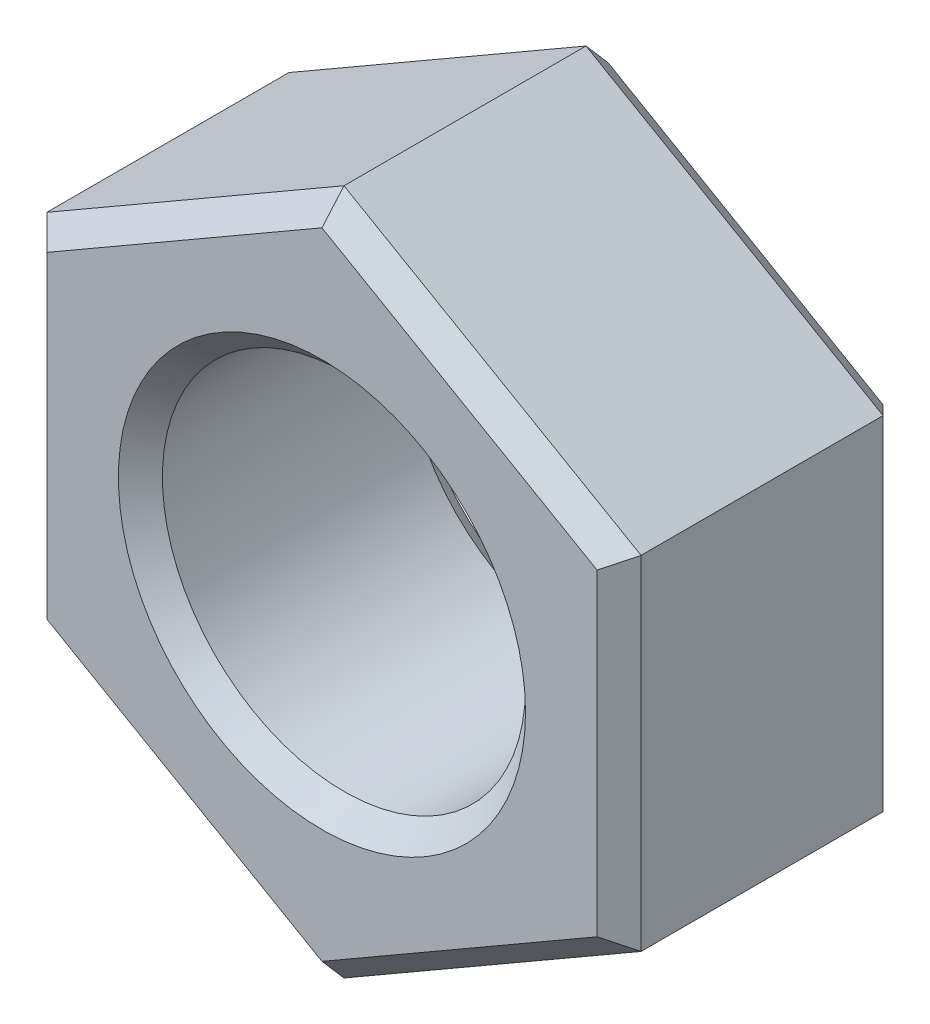
SolidWorks part; units mm, degrees
ref_plane "Front" through (0, 0, 0) normal (0, 0, 1) x (1, 0, 0)
ref_plane "Top" through (0, 0, 0) normal (0, 1, 0) x (1, 0, 0)
ref_plane "Right" through (0, 0, 0) normal (1, 0, 0) x (0, 0, -1)
sketch "Sketch1" plane through (0, 0, 0) normal (0, 0, 1) x (1, 0, 0)
  line L1 (2.7, -1.5588) -> (2.7, 1.5588)
  line L2 (2.7, 1.5588) -> (0, 3.1177)
  line L3 (0, 3.1177) -> (-2.7, 1.5588)
  line L4 (-2.7, 1.5588) -> (-2.7, -1.5588)
  line L5 (-2.7, -1.5588) -> (0, -3.1177)
  line L6 (0, -3.1177) -> (2.7, -1.5588)
  circle A0 centre (0, 0) radius 2.7 construction
  circle A1 centre (0, 0) radius 1.65
  dimension "D1" = 3.3
  dimension "D2" = 5.4
extrude "Boss-Extrude1" add sketch "Sketch1" along normal mid plane 2.6
chamfer "Deburs" distance 0.2 angle 45 14 edges at (1.65, 0, -1.3) (2.7, 0, -1.3) (1.35, 2.3383, -1.3) (-1.35, 2.3383, -1.3) (-2.7, 0, -1.3) (-1.35, -2.3383, -1.3) (1.35, -2.3383, -1.3) (1.65, 0, 1.3) (-1.35, -2.3383, 1.3) (-2.7, 0, 1.3) (-1.35, 2.3383, 1.3) (1.35, 2.3383, 1.3) (2.7, 0, 1.3) (1.35, -2.3383, 1.3)
equation "\"D1@Sketch1\"=\"Hardware Clearance Hole Diameter@Box Assy.Assembly\"+.15"
equation "\"D2@Sketch1\"=\"Nut Trap Diameter@Box Assy.Assembly\"-0.3mm"
equation "\"D1@Boss-Extrude1\"=\"Nut Trap Depth@Box Assy.Assembly\""
